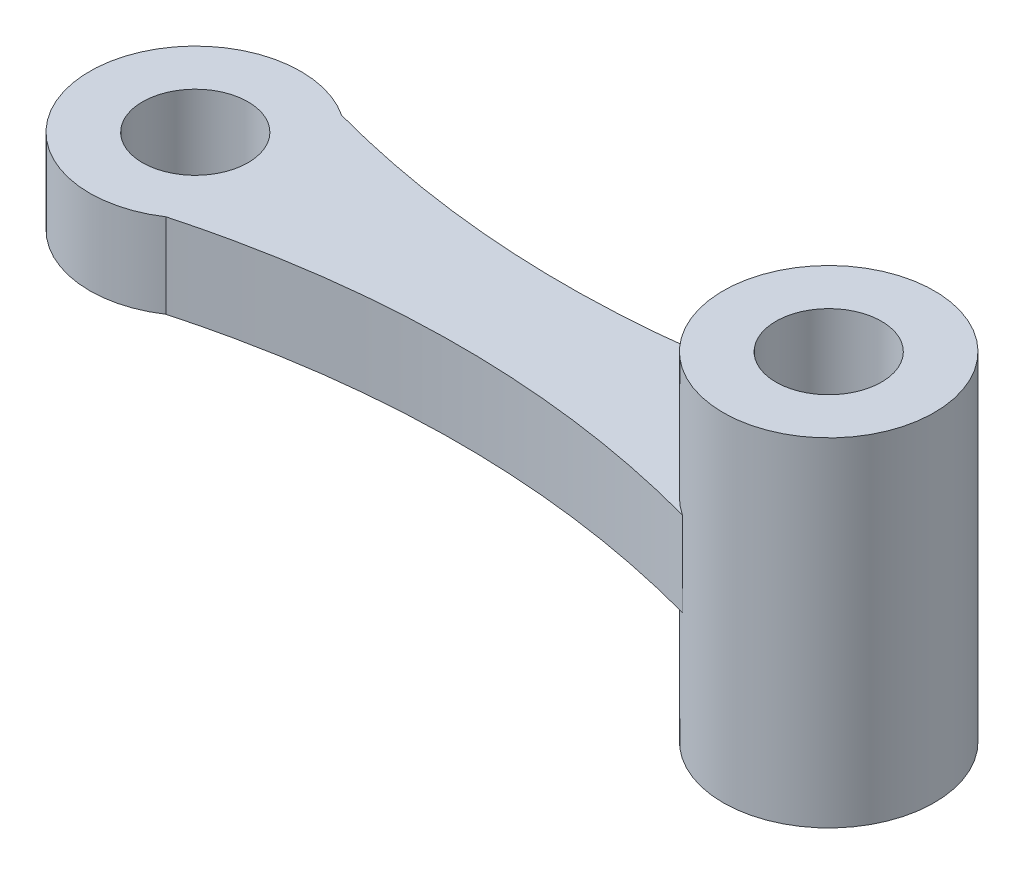
SolidWorks part; units mm, degrees
ref_plane "Front Plane" through (0, 0, 0) normal (0, 0, 1) x (1, 0, 0)
ref_plane "Top Plane" through (0, 0, 0) normal (0, 1, 0) x (1, 0, 0)
ref_plane "Right Plane" through (0, 0, 0) normal (1, 0, 0) x (0, 0, -1)
sketch "Sketch1" plane through (0, 0, 0) normal (0, 1, 0) x (1, 0, 0)
  line L0 (0, 0) -> (30, 0) construction
  line L1 (0, 5) -> (30, 5)
  line L2 (0, -5) -> (30, -5)
  arc A0 (0, 5) -> (0, -5) centre (0, 0) ccw
  arc A1 (30, -5) -> (30, 5) centre (30, 0) ccw
  circle A2 centre (0, 0) radius 2.5
  circle A3 centre (30, 0) radius 2.5
  point P3 (15, 0)
  dimension "D3" = 5
  dimension "D4" = 5
  dimension "D1" = 30
  dimension "D2" = 10
extrude "Boss-Extrude1" add sketch "Sketch1" along normal blind 4
ref_plane "Plane1" through (0, 2, 0) normal (0, 1, 0) x (1, 0, 0)
sketch "Sketch3" plane through (0, 2, 0) normal (0, 1, 0) x (1, 0, 0)
  circle A0 centre (30, 0) radius 5
  circle A1 centre (30, 0) radius 2.5
extrude "Boss-Extrude3" add sketch "Sketch3" along normal blind 8 and the other way blind 8
sketch "Sketch4" plane through (0, 4, 0) normal (0, 1, 0) x (1, 0, 0)
  line L0 (15, 5) -> (15, 0) construction
  line L1 (30, 5) -> (0, 5) construction
  line L3 (-5, 0) -> (35, 0) construction
  line L4 (11.3416, 2.5) -> (19.3123, 2.5) construction
  line L5 (15, 0) -> (15, -5) construction
  line L6 (0, -5) -> (30, -5) construction
  line L7 (11.3416, -2.5) -> (19.3123, -2.5) construction
  line L8 (0, -5) -> (30, -5)
  line L9 (0, 5) -> (30, 5)
  arc A0 (0, 5) -> (0, -5) centre (0, 0) ccw construction
  circle A1 centre (30, 0) radius 5 construction
  arc A2 (2.7717, 4.1615) -> (0, 5) centre (0, 0) ccw
  arc A3 (27.2283, -4.1615) -> (30, -5) centre (30, 0) ccw
  arc A4 (0, -5) -> (2.7717, -4.1615) centre (0, 0) ccw
  arc A5 (30, 5) -> (27.2283, 4.1615) centre (30, 0) ccw
  spline S0 degree 3 poles (2.7717, 4.1615) (6.8478, 3.0538) (15, 1.9462) (23.1522, 3.0538) (27.2283, 4.1615) knots 0.092389 0.092389 0.092389 0.092389 0.5 0.907611 0.907611 0.907611 0.907611
  spline S1 degree 3 poles (2.7717, -4.1615) (6.8478, -3.0538) (15, -1.9462) (23.1522, -3.0538) (27.2283, -4.1615) knots 0.092389 0.092389 0.092389 0.092389 0.5 0.907611 0.907611 0.907611 0.907611
extrude "Cut-Extrude1" cut sketch "Sketch4" against normal blind 10
